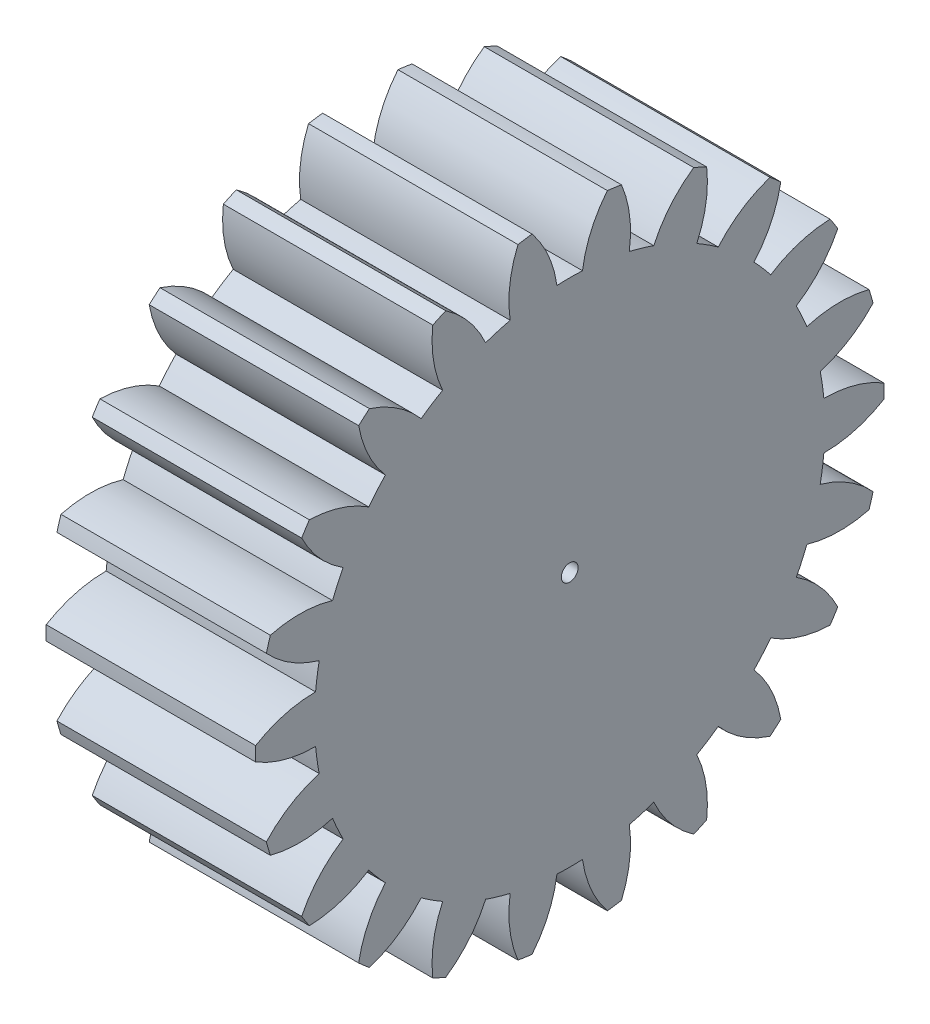
SolidWorks part; units mm, degrees
ref_plane "Plane1" through (0, 0, 0) normal (0, 0, 1) x (1, 0, 0)
ref_plane "Plane2" through (0, 0, 0) normal (0, 1, 0) x (1, 0, 0)
ref_plane "Plane3" through (0, 0, 0) normal (1, 0, 0) x (0, 0, -1)
sketch "HoldingSke" plane through (0, 0, 0) normal (0, 1, 0) x (1, 0, 0)
  line L0 (0, 0) -> (0.7417, -0.2997)
  line L1 (-15, 0) -> (100, 0) construction
  line L2 (0, 0) -> (-2.1039, 2.3779)
  line L3 (0, 0) -> (-11.863, 4.5341)
  line L4 (0, 0) -> (8.0072, 3.2351)
  line L5 (0, 0) -> (-46.8476, -17.4728)
  line L6 (0, 0) -> (-8.2896, -5.593)
  line L7 (-2.1039, 2.3779) -> (8.6586, 51.2059)
  line L8 (-76.2, 54.61) -> (-76.1, 54.61)
  line L9 (-71.009, 38.7566) -> (-53.1078, 45.2721)
  line L10 (-76.2, 71.12) -> (104.1128, 71.12)
  line L11 (0, 0) -> (-10, 0)
  line L12 (-76.2, 101.6) -> (-76.155, 101.6)
  line L13 (24.9733, 27.94) -> (52.9518, 28.4284)
  line L14 (24.9733, 27.94) -> (24.9743, 27.94)
  line L15 (24.9733, 27.94) -> (100.4006, 29.5858)
  line L16 (-63.627, -1.25) -> (-12.827, -1.25)
  circle A0 centre (0, 0) radius 0.4
  circle A1 centre (0, 0) radius 12.1865
  circle A2 centre (0, 0) radius 37.5
  circle A3 centre (0, 0) radius 0.4
  dimension "MHD" = 24.373
  dimension "Hub_dia" = 75
  dimension "Bore" = 0.8
  dimension "MBD" = 0.8
  dimension "Num_teeth" = 22
  dimension "Pitch" = 0.8
  dimension "Overall_len" = 50
  dimension "Show_teeth" = 22
  dimension "Thickness" = 10
  dimension "OAL" = 50.0001
  dimension "T_dim" = 0.1
  dimension "Ap" = 20
  dimension "H" = 19.05
  dimension "Pitch_radius" = 180.3128
  dimension "Width" = 10
  dimension "Backlash" = 0.045
  dimension "Addendum_fac" = 1
  dimension "Dedendum_fac" = 1.25
  dimension "Clearance_fac" = 0.25
  dimension "Dedendum_add" = 0.001
  dimension "Module" = 1.25
sketch "BasProSke" plane through (0, 0, 0) normal (0, 1, 0) x (1, 0, 0)
  line L0 (-10, 0) -> (60, 0) construction
  line L1 (0, 0) -> (0, 15)
  line L2 (0, 0) -> (10, 0)
  line L3 (10, 0) -> (10, 15)
  line L4 (10, 15) -> (0, 15)
  dimension "Thickness" = 10
  dimension "Diameter" = 30
revolve "Base-Revolve" add sketch "BasProSke" angle 360 about L0
sketch "TooCutSke" plane through (0, 0, 0) normal (1, 0, 0) x (0, 0, -1)
  line L1 (0, 0) -> (0, 107) construction
  line L2 (0, 0) -> (-1.0596, 13.7091) construction
  line L3 (0, 0) -> (-3.9052, 27.1614) construction
  line L4 (-1.0596, 13.7091) -> (-1.9526, 13.5807) construction
  arc A0 (0.6099, 12.1712) -> (-0.6099, 12.1712) centre (0, 0) ccw
  arc A1 (1.8166, 14.9152) -> (-1.8166, 14.9152) centre (0, 0) ccw
  circle A2 centre (0, 0) radius 13.75 construction
  circle A3 centre (0, 0) radius 12.9208 construction
  arc A4 (-0.6099, 12.1712) -> (-1.8166, 14.9152) centre (-6.0574, 11.4129) ccw
  arc A5 (1.8166, 14.9152) -> (0.6099, 12.1712) centre (6.0574, 11.4129) ccw
  dimension "Root_dia" = 24.373
  dimension "Overcut_dia" = 30.0508
  dimension "Pitch_dia" = 27.5
  dimension "Base_dia" = 25.8415
  dimension "Flank_rad" = 5.5
  dimension "Half_ang" = 8.182
  dimension "Half_CT" = 0.9022
extrude "ToothCut" cut sketch "TooCutSke" along normal through all
fillet "Breaks" [suppressed] radius 0.025
fillet "RootFillets" [suppressed] radius 0.3135
pattern_circular "TeethCuts" count 22 every 16.364 about axis through (-10, 0, 0) along (1, 0, 0) of "ToothCut", "RootFillets", "Breaks"
sketch "HubNeaOneSke" plane through (0, 0, 0) normal (-1, 0, 0) x (0, 0, 1)
  circle A0 centre (0, 0) radius 12.1865
  dimension "Diameter" = 24.373
extrude "HubNearOne" [suppressed] add sketch "HubNeaOneSke" along normal blind 40.0001
sketch "HubNeaBotSke" plane through (0, 0, 0) normal (-1, 0, 0) x (0, 0, 1)
  circle A0 centre (0, 0) radius 12.1865
  dimension "Diameter" = 24.373
extrude "HubNearBoth" [suppressed] add sketch "HubNeaBotSke" along normal blind 20
ref_plane "FarPln" through (10, 0, 0) normal (1, 0, 0) x (0, 0, -1)
sketch "HubFarSke" plane through (10, 0, 0) normal (1, 0, 0) x (0, 0, -1)
  circle A0 centre (0, 0) radius 12.1865
  dimension "Diameter" = 24.373
extrude "HubFar" [suppressed] add sketch "HubFarSke" along normal blind 20
sketch "BorSke" plane through (0, 0, 0) normal (1, 0, 0) x (0, 0, -1)
  circle A0 centre (0, 0) radius 0.4
  dimension "Diameter" = 0.8
extrude "Bore" cut sketch "BorSke" along normal mid plane 100.0001
sketch "KeySke" plane through (0, 0, 0) normal (1, 0, 0) x (0, 0, -1)
  line L0 (-0.05, 0) -> (-0.05, 0.5)
  line L1 (-0.05, 0.5) -> (0.05, 0.5)
  line L2 (0.05, 0.5) -> (0.05, 0)
  line L3 (0, 0) -> (0, 34) construction
  line L4 (-0.05, 0) -> (0.05, 0)
  dimension "Offset" = 0.5
  dimension "Width" = 0.1
extrude "Keyway" [suppressed] cut sketch "KeySke" along normal mid plane 100.0001
pattern_circular "Keyway2" [suppressed] count 2 every 90 about axis through (-10, 0, 0) along (1, 0, 0)
equation "' \"Module@HoldingSke\" = 6.35"
equation "' \"Num_teeth@HoldingSke\" = 12"
equation "' \"Ap@HoldingSke\" =  20"
equation "' \"Ap@HoldingSke\" = 20"
equation "' \"Width@HoldingSke\" = 0.5 * 25.4"
equation "' \"Hub_dia@HoldingSke\"= 1 * 25.4"
equation "' \"Hub_dia@HoldingSke\" = 1 * 25.4"
equation "' \"Overall_len@HoldingSke\" = 1.0 * 25.4"
equation "' \"Bore@HoldingSke\" = 0.75 * 25.4"
equation "' \"T_dim@HoldingSke\" = 0.1 * 25.4"
equation "' \"Width@KeySke\" = 0.25 * 25.4"
equation "' \"Show_teeth@HoldingSke\" = 13"
equation "' \"Backlash@HoldingSke\" = 0.009 * 25.4"
equation "' \"Addendum_fac@HoldingSke\" = 1.0"
equation "' \"Dedendum_fac@HoldingSke\" = 1.25"
equation "' \"Dedendum_add@HoldingSke\" = 0.00005 * 25.4"
equation "' \"Clearance_fac@HoldingSke\" = 0.25"
equation "\"Pitch@HoldingSke\" = 1 / \"Module@HoldingSke\""
equation "\"Overcut_dia@TooCutSke\" = (\"Num_teeth@HoldingSke\" + 2 * \"Addendum_fac@HoldingSke\") / \"Pitch@HoldingSke\" + 0.002 * 25.4"
equation "\"Pitch_dia@TooCutSke\" = \"Num_teeth@HoldingSke\" / \"Pitch@HoldingSke\""
equation "\"Base_dia@TooCutSke\" = \"Num_teeth@HoldingSke\" / \"Pitch@HoldingSke\" * cos((\"Ap@HoldingSke\"  * 3.14159265 / 180))"
equation "\"Root_dia@TooCutSke\" = (\"Num_teeth@HoldingSke\" + 2) / \"Pitch@HoldingSke\" - 2 * (\"Addendum_fac@HoldingSke\" + \"Dedendum_fac@HoldingSke\") / \"Pitch@HoldingSke\" - \"Dedendum_add@HoldingSke\" * 2"
equation "\"Half_ang@TooCutSke\" = 180 / \"Num_teeth@HoldingSke\""
equation "\"Half_CT@TooCutSke\" = \"Num_teeth@HoldingSke\" / \"Pitch@HoldingSke\" * sin((3.14159265 / 2 / \"Num_teeth@HoldingSke\")) / 2 - 7 * \"Backlash@HoldingSke\" / 4"
equation "\"Flank_rad@TooCutSke\" = \"Num_teeth@HoldingSke\" / \"Pitch@HoldingSke\" / 5"
equation "\"Radius@RootFillets\" = \"Clearance_fac@HoldingSke\" / \"Pitch@HoldingSke\" + \"Dedendum_add@HoldingSke\""
equation "\"Break_rad@Breaks\" = 0.02 / \"Pitch@HoldingSke\""
equation "\"Thickness@HoldingSke\" = \"Width@HoldingSke\""
equation "\"OAL@HoldingSke\" = \"Thickness@HoldingSke\""
equation "\"MHD@HoldingSke\" = (\"Num_teeth@HoldingSke\" + 2) / \"Pitch@HoldingSke\" - 2 * (\"Addendum_fac@HoldingSke\" + \"Dedendum_fac@HoldingSke\")  / \"Pitch@HoldingSke\" - \"Dedendum_add@HoldingSke\" * 2"
equation "\"MBD@HoldingSke\" = (\"Num_teeth@HoldingSke\" + 2) / \"Pitch@HoldingSke\" - 2 * (\"Addendum_fac@HoldingSke\" + \"Dedendum_fac@HoldingSke\")  / \"Pitch@HoldingSke\" - \"Dedendum_add@HoldingSke\" * 2 - 0.002 * 25.4"
equation "\"MHD@HoldingSke\" = ((sgn( \"MHD@HoldingSke\" - \"Hub_dia@HoldingSke\" )-1)*( \"MHD@HoldingSke\" - \"Hub_dia@HoldingSke\" ))/-2+ \"Hub_dia@HoldingSke\""
equation "\"MBD@HoldingSke\" = ((sgn( \"MBD@HoldingSke\" - \"Bore@HoldingSke\" )-1)*( \"MBD@HoldingSke\" - \"Bore@HoldingSke\" ))/-2+ \"Bore@HoldingSke\""
equation "\"OAL@HoldingSke\" = ((sgn( \"OAL@HoldingSke\" - \"Overall_len@HoldingSke\" )+1)*( \"OAL@HoldingSke\" - \"Overall_len@HoldingSke\" ))/2 + \"Overall_len@HoldingSke\" + 0.000002 * 25.4"
equation "\"Num_teeth@TeethCuts\" = int( \"Show_teeth@HoldingSke\" ) + 1"
equation "\"Num_teeth@TeethCuts\" = ((sgn( \"Num_teeth@TeethCuts\" - \"Num_teeth@HoldingSke\" )-1)*( \"Num_teeth@TeethCuts\" - \"Num_teeth@HoldingSke\" ))/-2+ \"Num_teeth@HoldingSke\""
equation "\"Num_teeth@TeethCuts\" = ((sgn( \"Num_teeth@TeethCuts\" - 2.0)+1)*( \"Num_teeth@TeethCuts\" - 2.0))/2 +2.0"
equation "\"Angle@TeethCuts\" = 360.0 / \"Num_teeth@HoldingSke\""
equation "\"Diameter@BasProSke\" = (\"Num_teeth@HoldingSke\" + 2 * \"Addendum_fac@HoldingSke\") / \"Pitch@HoldingSke\""
equation "\"Thickness@BasProSke\"  = \"Thickness@HoldingSke\""
equation "' \"Fillet_rad@BasProSke\" =  \"Thickness@HoldingSke\" * 0.05"
equation "' \"Fillet_rad@BasProSke\" = \"Thickness@HoldingSke\" * 0.05"
equation "\"MHD@HoldingSke\" = ((sgn( \"MHD@HoldingSke\" - \"Root_dia@TooCutSke\" )-1)*( \"MHD@HoldingSke\" - \"Root_dia@TooCutSke\" ))/-2+ \"Root_dia@TooCutSke\""
equation "\"Diameter@HubNeaOneSke\" = \"MHD@HoldingSke\""
equation "\"Length@HubNearOne\" = \"OAL@HoldingSke\" - \"Thickness@BasProSke\""
equation "\"Diameter@HubNeaBotSke\" = \"MHD@HoldingSke\""
equation "\"Length@HubNearBoth\" = ( \"OAL@HoldingSke\" - \"Thickness@BasProSke\" ) / 2.0"
equation "\"Thickness@FarPln\" = \"Thickness@BasProSke\""
equation "\"Diameter@HubFarSke\" = \"MHD@HoldingSke\""
equation "\"Length@HubFar\" = ( \"OAL@HoldingSke\" - \"Thickness@BasProSke\" ) / 2.0"
equation "\"Diameter@BorSke\" = \"MBD@HoldingSke\""
equation "\"D1@Bore\" = \"OAL@HoldingSke\" * 2.0"
equation "\"D1@Keyway\" = \"OAL@HoldingSke\" * 2.0"
equation "\"Offset@KeySke\" = \"T_dim@HoldingSke\" + \"MBD@HoldingSke\" / 2.0"
